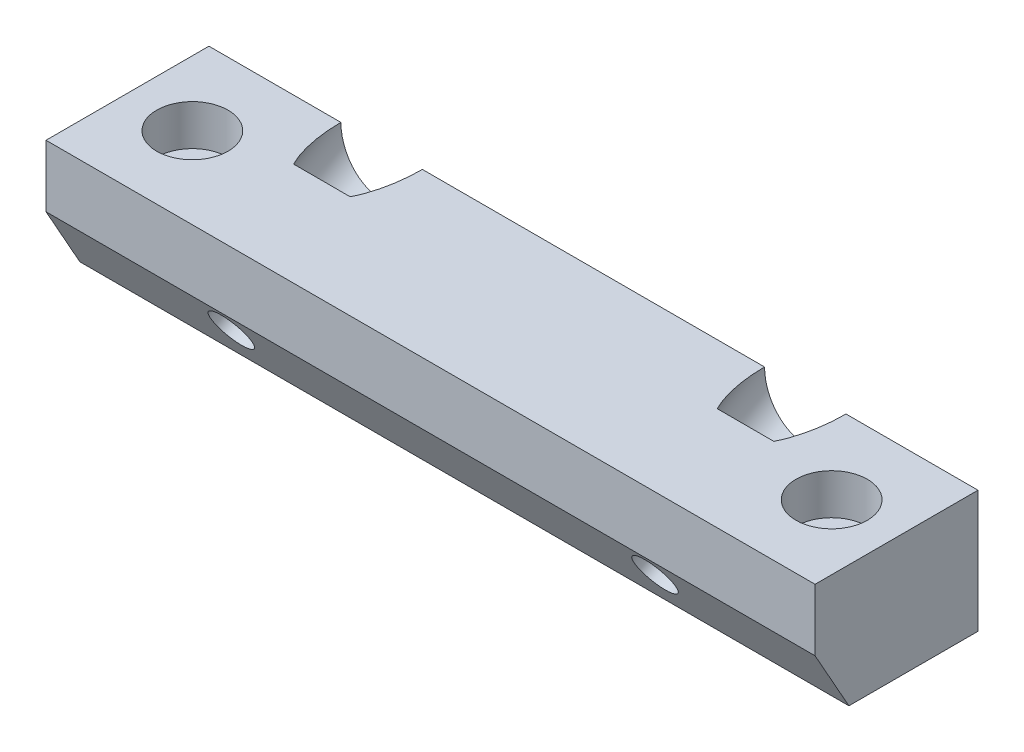
SolidWorks part; units mm, degrees
material "6061-T6 (SS)"
ref_plane "Front Plane" through (0, 0, 0) normal (0, 0, 1) x (1, 0, 0)
ref_plane "Top Plane" through (0, 0, 0) normal (0, 1, 0) x (1, 0, 0)
ref_plane "Right Plane" through (0, 0, 0) normal (1, 0, 0) x (0, 0, -1)
sketch "Sketch1" plane through (0, 0, 0) normal (1, 0, 0) x (0, 0, -1)
  line L0 (0, 0) -> (0, 19.05)
  line L1 (0, 19.05) -> (-25.4, 19.05)
  line L2 (-25.4, 19.05) -> (-25.4, 9.398)
  line L3 (-25.4, 9.398) -> (-20.1213, 0)
  line L4 (-20.1213, 0) -> (0, 0)
  dimension "D1" = 25.4
  dimension "D2" = 19.05
  dimension "D3" = 150.678
  dimension "D4" = 9.652
extrude "Boss-Extrude1" add sketch "Sketch1" along normal blind 119.888
sketch "Sketch2" plane through (0, 19.05, 0) normal (0, 1, 0) x (1, 0, 0)
  line L0 (59.944, 0) -> (59.944, -25.4) construction
  line L1 (119.888, 0) -> (0, 0) construction
  line L2 (119.888, -25.4) -> (0, -25.4) construction
  line L4 (0, 0) -> (0, -25.4) construction
  line L5 (0, -12.7) -> (119.888, -12.7) construction
  line L6 (119.888, 0) -> (119.888, -25.4) construction
  point P6 (109.7724, -12.7)
  point P14 (10.1156, -12.7)
  dimension "D1" = 49.8285
hole_wizard "CBORE for 1/4 Socket Head Cap Screw1" positions "Sketch2" profile "Sketch3" counterbore size "1/4" standard "ANSI Inch" end condition through all
sketch "Sketch3" plane through (10.1156, 19.05, 12.7) normal (1, 0, 0) x (0, 0, 1)
  line L0 (0, 0) -> (0, 19.05)
  line L1 (0, 19.05) -> (3.3782, 19.05)
  line L3 (3.3782, 19.05) -> (3.3782, 6.35)
  line L4 (3.3782, 6.35) -> (5.5562, 6.35)
  line L5 (5.5562, 6.35) -> (5.5563, 0)
  line L7 (5.5563, 0) -> (0, 0)
  line L11 (0, -6.35) -> (0, 107.95) construction
  dimension "Thru Hole Dia." = 6.7564
  dimension "Thru Hole Depth" = 19.05
  dimension "C'Bore Dia." = 11.1125
  dimension "C'Bore Depth" = 6.35
ref_plane "Plane1" through (0, 4.5686, -8.1339) normal (0, -0.4897, 0.8719) x (1, 0, 0)
sketch "Sketch4" plane through (0, 4.5686, -8.1339) normal (0, -0.4897, 0.8719) x (1, 0, 0)
  line L0 (119.888, 16.6093) -> (0, 16.6093) construction
  line L1 (59.944, 16.6093) -> (59.944, 19.9856) construction
  point P0 (92.964, 16.6093)
  point P5 (26.924, 16.6093)
  dimension "D1" = 33.02
hole_wizard "5/16-18 Tapped Hole1" positions "Sketch4" profile "Sketch5" tap size "5/16-18" standard "ANSI Inch" end condition through all
sketch "Sketch5" plane through (92.964, 19.05, 0) normal (1, 0, 0) x (0, 0.8719, 0.4897)
  line L0 (0, 0) -> (0, 31.4749)
  line L1 (0, 31.4749) -> (3.2639, 31.4749)
  line L2 (3.2639, 31.4749) -> (3.2639, 0)
  line L5 (3.2639, 0) -> (0, 0)
  line L11 (0, -6.35) -> (0, 107.95) construction
  dimension "Thru Tap Drill Dia." = 6.5278
  dimension "Thru Tap Drill Depth" = 31.4749
cosmetic thread "Hole Thread1" parameters "D2"=7.9375
cosmetic thread "Hole Thread2" parameters "D2"=7.9375
ref_plane "Plane2" through (0, 0.5882, -1.0472) normal (0, -0.4897, 0.8719) x (1, 0, 0)
sketch "Sketch6" plane through (0, 0.5882, -1.0472) normal (0, -0.4897, 0.8719) x (1, 0, 0)
  line L0 (59.944, 20.6328) -> (59.944, 33.2858) construction
  line L1 (119.888, 20.6328) -> (0, 20.6328) construction
  circle A0 centre (26.924, 16.6093) radius 6.35
  circle A1 centre (92.964, 16.6093) radius 6.35
  dimension "D1" = 12.7
extrude "Cut-Extrude1" cut sketch "Sketch6" against normal through all
